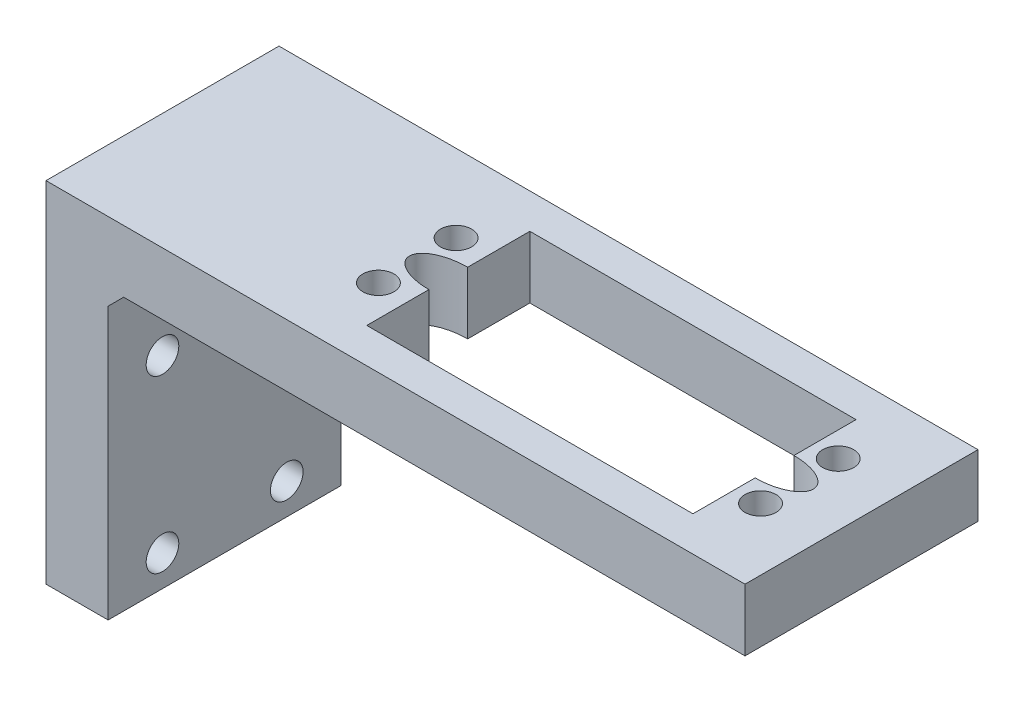
SolidWorks part; units mm, degrees
material "ABS"
ref_plane "前基準面" through (0, 0, 0) normal (0, 0, 1) x (1, 0, 0)
ref_plane "上基準面" through (0, 0, 0) normal (0, 1, 0) x (1, 0, 0)
ref_plane "右基準面" through (0, 0, 0) normal (1, 0, 0) x (0, 0, -1)
sketch "草圖1" plane through (0, 0, 0) normal (0, 1, 0) x (1, 0, 0)
  line L1 (0, 0) -> (82, 0)
  line L2 (0, 0) -> (0, 30)
  line L3 (0, 30) -> (82, 30)
  line L4 (82, 0) -> (82, 30)
  dimension "D1" = 82
  dimension "D2" = 30
extrude "填料-伸長1" add sketch "草圖1" along normal blind 8
sketch "草圖2" plane through (0, 8, 0) normal (0, 1, 0) x (1, 0, 0)
  line L1 (28.8, 25.5) -> (70.8, 25.5)
  line L3 (28.8, 4.5) -> (70.8, 4.5)
  line L6 (82, 30) -> (0, 30) construction
  line L7 (28.8, 25.5) -> (28.8, 17.5)
  line L8 (70.8, 25.5) -> (70.8, 17.5)
  line L9 (70.8, 12.5) -> (70.8, 4.5)
  line L10 (28.8, 12.5) -> (28.8, 4.5)
  line L11 (0, 30) -> (0, 0) construction
  line L12 (82, 0) -> (82, 30) construction
  circle A0 centre (74, 20) radius 2
  circle A1 centre (74, 10) radius 2
  circle A2 centre (24.8, 20) radius 2
  circle A3 centre (24.8, 10) radius 2
  ellipse E0 centre (70.8, 15) end of major axis (75.8, 15) minor radius 2.5 (70.8, 12.5) -> (70.8, 17.5) ccw
  ellipse E1 centre (28.8, 15) end of major axis (33.8, 15) minor radius 2.5 (28.8, 17.5) -> (28.8, 12.5) ccw
  dimension "D4" = 10
  dimension "D1" = 21
  dimension "D2" = 42
  dimension "D3" = 4.5
  dimension "D5" = 10
  dimension "D6" = 10
  dimension "D7" = 10
  dimension "D8" = 5
  dimension "D9" = 5
  dimension "D10" = 10
  dimension "D11" = 8
  dimension "D12" = 10
  dimension "D13" = 8
  dimension "24.8" = 24.8
  dimension "D15" = 8
  dimension "D16" = 28.8
extrude "除料-伸長1" cut sketch "草圖2" against normal blind 8
sketch "草圖4" plane through (0, 8, 0) normal (0, 1, 0) x (1, 0, 0)
  line L0 (0, 30) -> (0, 0)
  line L9 (0, 0) -> (-8, 0)
  line L10 (-8, 0) -> (-8, 30)
  line L11 (-8, 30) -> (0, 30)
  dimension "D1" = 8
extrude "填料-伸長2" add sketch "草圖4" against normal blind 45
sketch "草圖14" plane through (0, 0, 0) normal (0, 0, 1) x (1, 0, 0)
  line L0 (0, 0) -> (0, -2)
  line L1 (0, -37) -> (0, 0) construction
  line L2 (0, -2) -> (2, 0)
  line L3 (0, 0) -> (82, 0) construction
  line L4 (2, 0) -> (0, 0)
  dimension "D1" = 2
  dimension "D2" = 2
extrude "填料-伸長5" add sketch "草圖14" against normal blind 30
sketch "草圖15" plane through (0, 0, 0) normal (1, 0, 0) x (0, 0, -1)
  line L0 (0, -37) -> (30, -37) construction
  line L1 (0, -37) -> (0, -2) construction
  circle A0 centre (7, -33) radius 2.1
  circle A5 centre (7, -11) radius 2.1
  circle A13 centre (23, -11) radius 2.1
  circle A16 centre (23, -33) radius 2.1
  circle A19 centre (15, -11) radius 2.1 [skipped]
  circle A20 centre (15, -33) radius 2.1 [skipped]
  dimension "D1" = 4
  dimension "D2" = 22
  dimension "D3" = 4.2
  dimension "D4" = 4.2
  dimension "D6" = 7
  dimension "D7" = 3
extrude "除料-伸長2" cut sketch "草圖15" against normal blind 10
